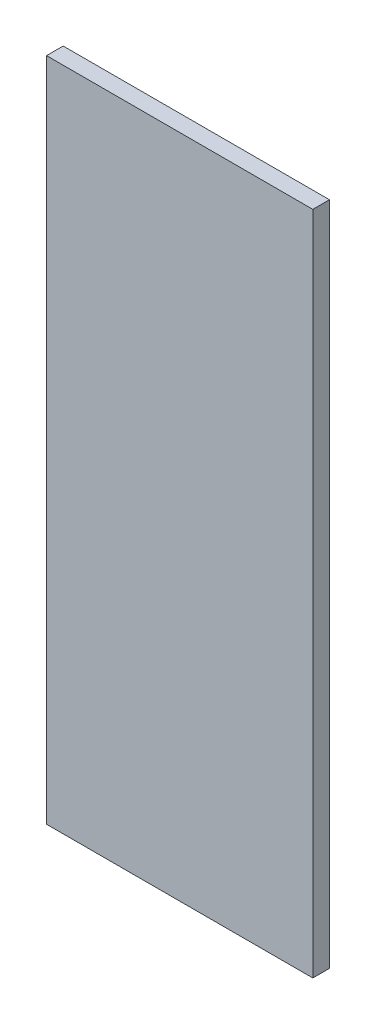
SolidWorks part; units mm, degrees
ref_plane "Front Plane" through (0, 0, 0) normal (0, 0, 1) x (1, 0, 0)
ref_plane "Top Plane" through (0, 0, 0) normal (0, 1, 0) x (1, 0, 0)
ref_plane "Right Plane" through (0, 0, 0) normal (1, 0, 0) x (0, 0, -1)
sketch "Sketch1" plane through (0, 0, 0) normal (0, 0, 1) x (1, 0, 0)
  line L1 (0, 0) -> (203.2, 0)
  line L2 (0, 0) -> (0, -508)
  line L3 (0, -508) -> (203.2, -508)
  line L4 (203.2, 0) -> (203.2, -508)
  dimension "D1" = 203.2
  dimension "D2" = 508
extrude "Boss-Extrude1" add sketch "Sketch1" along normal blind 12.7
